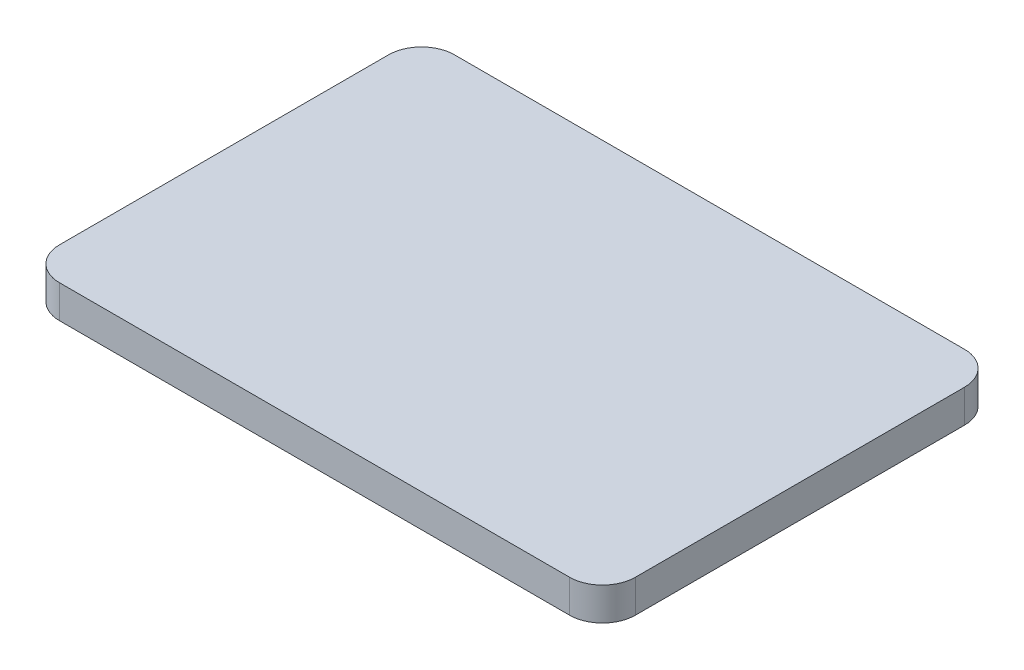
SolidWorks part; units mm, degrees
ref_plane "Front Plane" through (0, 0, 0) normal (0, 0, 1) x (1, 0, 0)
ref_plane "Top Plane" through (0, 0, 0) normal (0, 1, 0) x (1, 0, 0)
ref_plane "Right Plane" through (0, 0, 0) normal (1, 0, 0) x (0, 0, -1)
sketch "Szkic1" plane through (0, 0, 0) normal (0, 1, 0) x (1, 0, 0)
  line L0 (0, 1) -> (0, 11)
  line L1 (1, 12) -> (16.5, 12)
  line L2 (17.5, 11) -> (17.5, 1)
  line L3 (16.5, 0) -> (1, 0)
  arc A0 (0, 11) -> (1, 12) centre (1, 11) cw
  arc A1 (16.5, 12) -> (17.5, 11) centre (16.5, 11) cw
  arc A2 (17.5, 1) -> (16.5, 0) centre (16.5, 1) cw
  arc A3 (0, 1) -> (1, 0) centre (1, 1) ccw
  point P7 (0, 12)
  point P10 (17.5, 12)
  point P13 (17.5, 0)
  point P16 (0, 0)
  dimension "D3" = 1
  dimension "D1" = 17.5
  dimension "D2" = 12
extrude "Dodanie-wyciągnięcie3" add sketch "Szkic1" along normal blind 1
sketch "Szkic2" plane through (0, 1, 0) normal (0, 1, 0) x (1, 0, 0)
  line L0 (1, 1) -> (1, 11) construction
  line L1 (1, 11) -> (16.5, 11) construction
  line L2 (16.5, 11) -> (16.5, 1) construction
  line L3 (16.5, 1) -> (1, 1) construction
  line L4 (8.75, 12) -> (8.75, 0) construction
  line L5 (16.5, 12) -> (1, 12) construction
  line L6 (1, 0) -> (16.5, 0) construction
  line L7 (17.5, 6) -> (0, 6) construction
  line L8 (17.5, 1) -> (17.5, 11) construction
  line L9 (0, 11) -> (0, 1) construction
